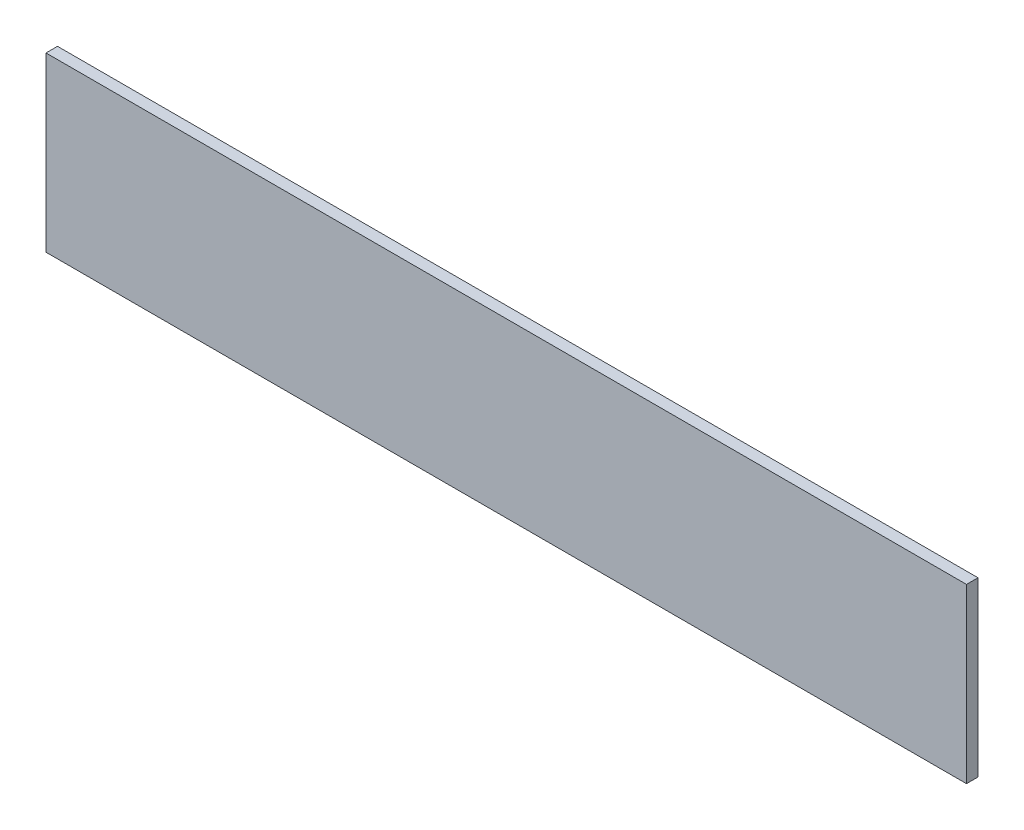
SolidWorks part; units mm, degrees
ref_plane "Piano frontale" through (0, 0, 0) normal (0, 0, 1) x (1, 0, 0)
ref_plane "Piano superiore" through (0, 0, 0) normal (0, 1, 0) x (1, 0, 0)
ref_plane "Piano destro" through (0, 0, 0) normal (1, 0, 0) x (0, 0, -1)
sketch "Schizzo1" plane through (0, 0, 0) normal (0, 0, 1) x (1, 0, 0)
  line L1 (0, 0) -> (160, 0)
  line L2 (0, 0) -> (0, 30)
  line L3 (0, 30) -> (160, 30)
  line L4 (160, 0) -> (160, 30)
  dimension "D1" = 30
  dimension "D2" = 160
extrude "Estrusione-Estrusione1" add sketch "Schizzo1" along normal blind 2
